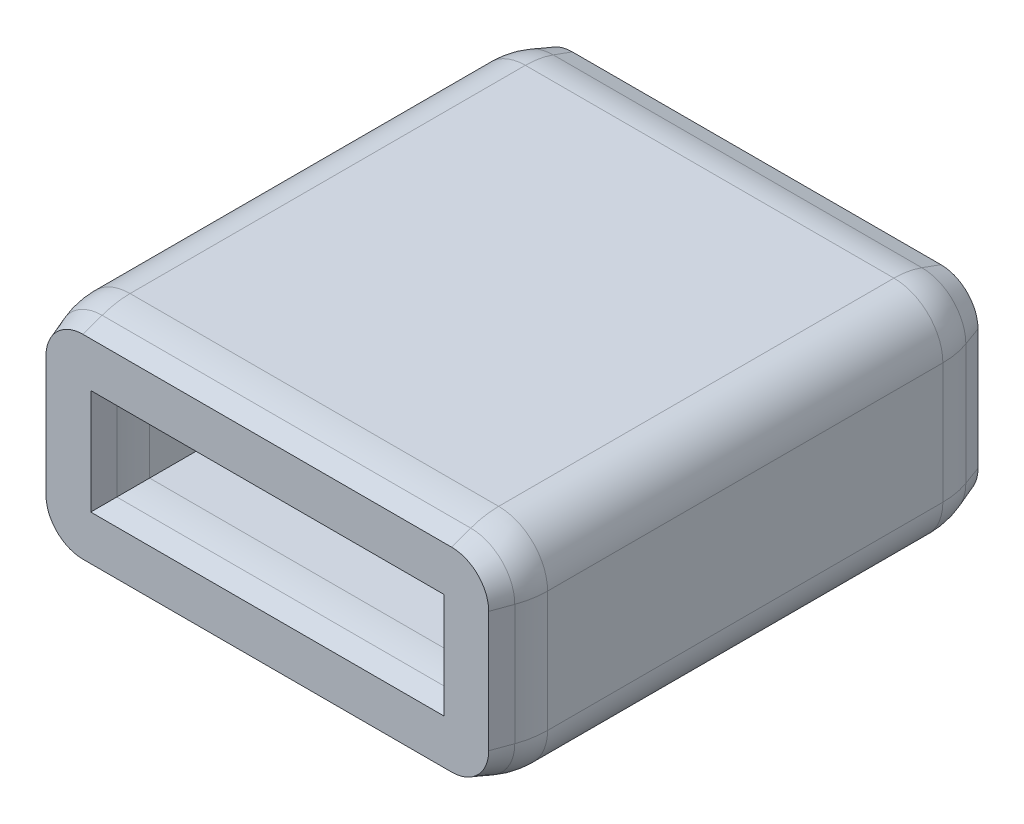
SolidWorks part; units mm, degrees
ref_plane "Front Plane" through (0, 0, 0) normal (0, 0, 1) x (1, 0, 0)
ref_plane "Top Plane" through (0, 0, 0) normal (0, 1, 0) x (1, 0, 0)
ref_plane "Right Plane" through (0, 0, 0) normal (1, 0, 0) x (0, 0, -1)
sketch "Profile Sketch" plane through (0, 0, 0) normal (0, 0, 1) x (1, 0, 0)
  line L0 (0, 1.25) -> (0, 3.35) construction
  line L1 (-5.05, -1.25) -> (5.05, -1.25)
  line L2 (-5.05, -1.25) -> (-5.05, 1.25)
  line L3 (-5.05, 1.25) -> (5.05, 1.25)
  line L4 (5.05, -1.25) -> (5.05, 1.25)
  line L5 (-5.05, -1.25) -> (5.05, 1.25) construction
  line L6 (-5.05, 1.25) -> (5.05, -1.25) construction
  line L7 (-7.15, -3.35) -> (7.15, -3.35)
  line L8 (-7.15, -3.35) -> (-7.15, 3.35)
  line L9 (-7.15, 3.35) -> (7.15, 3.35)
  line L10 (7.15, -3.35) -> (7.15, 3.35)
  line L11 (-7.15, -3.35) -> (7.15, 3.35) construction
  line L12 (-7.15, 3.35) -> (7.15, -3.35) construction
  line L13 (-5.05, 0) -> (-7.15, 0) construction
  point P0 (0, 0)
  point P6 (0, 0)
  dimension "D1" = 10.1
  dimension "D2" = 2.1
  dimension "D3" = 2.5
extrude "Profile Extrude" add sketch "Profile Sketch" along normal blind 15
fillet "Outside Corner Fillets" radius 1.5 4 edges at (7.15, 3.35, 7.5) (7.15, -3.35, 7.5) (-7.15, 3.35, 7.5) (-7.15, -3.35, 7.5)
fillet "Corner Fillets" [suppressed] radius 1
fillet "Inlet Fillets" [suppressed] radius 1
chamfer "End 1 Chamfer" distance 1 angle 20 12 edges at (6.7107, 2.9107, 0) (7.15, 0, 0) (6.7107, -2.9107, 0) (0, -3.35, 0) (-6.7107, -2.9107, 0) (-7.15, 0, 0) (-6.7107, 2.9107, 0) (0, 3.35, 0) (5.05, 0, 15) (0, 1.25, 15) (-5.05, 0, 15) (0, -1.25, 15)
chamfer "End 2 Chamfer" distance 1 angle 20 12 edges at (0, -3.35, 15) (6.7107, -2.9107, 15) (-6.7107, -2.9107, 15) (7.15, 0, 15) (-7.15, 0, 15) (6.7107, 2.9107, 15) (-6.7107, 2.9107, 15) (0, 3.35, 15) (5.05, 0, 0) (0, 1.25, 0) (-5.05, 0, 0) (0, -1.25, 0)
fillet "Transition Fillets" radius 2.5 24 edges at (6.7107, 2.9107, 1) (7.15, 0, 1) (6.7107, -2.9107, 1) (0, -3.35, 1) (-6.7107, -2.9107, 1) (-7.15, 0, 1) (-6.7107, 2.9107, 1) (0, 3.35, 1) (-6.7107, 2.9107, 14) (-7.15, 0, 14) (-6.7107, -2.9107, 14) (0, -3.35, 14) (6.7107, -2.9107, 14) (7.15, 0, 14) (6.7107, 2.9107, 14) (0, 3.35, 14) (0, 1.25, 1) (0, 1.25, 14) (5.05, 0, 14) (-5.05, 0, 14) (0, -1.25, 14) (-5.05, 0, 1) (0, -1.25, 1) (5.05, 0, 1)
